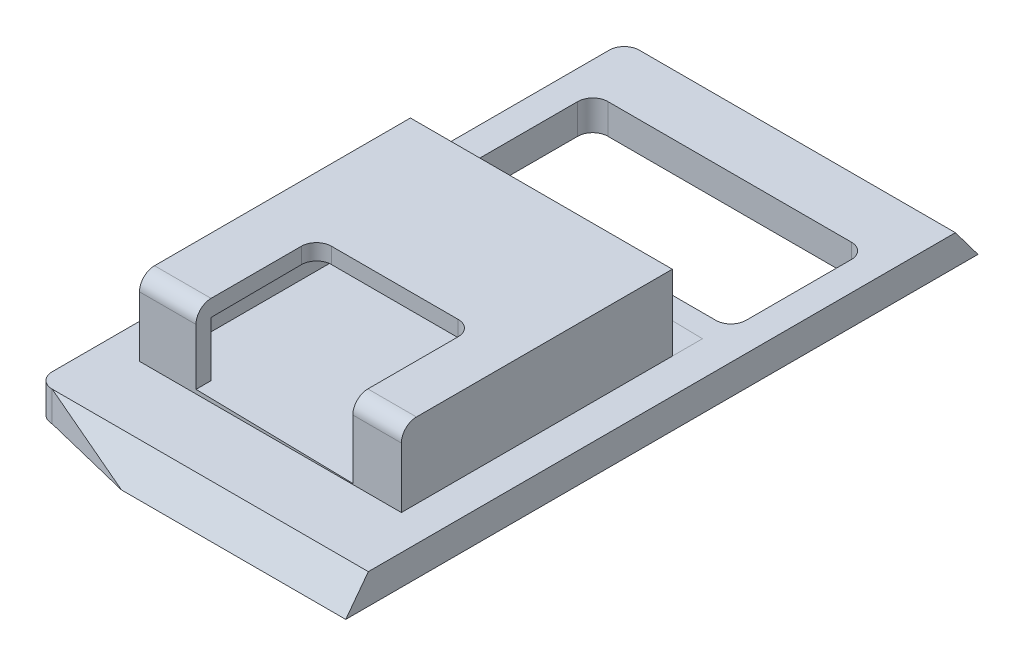
SolidWorks part; units mm, degrees
ref_plane "Alzado" through (0, 0, 0) normal (0, 0, 1) x (1, 0, 0)
ref_plane "Planta" through (0, 0, 0) normal (0, 1, 0) x (1, 0, 0)
ref_plane "Vista lateral" through (0, 0, 0) normal (1, 0, 0) x (0, 0, -1)
sketch "Croquis1" plane through (0, 0, 0) normal (0, 1, 0) x (1, 0, 0)
  line L1 (0, 0) -> (22, 0)
  line L2 (0, 0) -> (0, 39)
  line L3 (0, 39) -> (22, 39)
  line L4 (22, 0) -> (22, 39)
  line L5 (1.9117, 26) -> (20.0883, 26)
  line L6 (1.9117, 26) -> (1.9117, 35)
  line L7 (1.9117, 35) -> (20.0883, 35)
  line L8 (20.0883, 26) -> (20.0883, 35)
  line L22 (2.3, 4.4967) -> (19.7, 4.4967)
  line L23 (19.7, 4.4967) -> (19.7, 22.4967)
  line L24 (19.7, 22.4967) -> (18.7, 22.4967)
  line L25 (18.7, 22.4967) -> (18.7, 5.4967)
  line L26 (18.7, 5.4967) -> (3.3, 5.4967)
  line L27 (3.3, 5.4967) -> (3.3, 22.4967)
  line L28 (2.3, 4.4967) -> (2.3, 22.4967)
  line L29 (2.3, 22.4967) -> (3.3, 22.4967)
  dimension "D1" = 22
  dimension "D2" = 39
  dimension "D3" = 4
  dimension "D6" = 9
extrude "Saliente-Extruir1" add sketch "Croquis1" along normal blind 2
fillet "Redondeo1" radius 1 2 edges at (0, 1, 0) (0, 1, -39)
fillet "Redondeo2" radius 1 4 edges at (20.0883, 1, -26) (20.0883, 1, -35) (1.9117, 1, -26) (1.9117, 1, -35)
ref_plane "Plano4" through (3.3, 2, -22.4967) normal (-1, 0, 0) x (0, 0, 1)
sketch "Croquis8" plane through (0, 2, 0) normal (0, 1, 0) x (1, 0, 0)
  line L0 (2.3, 22.4967) -> (3.3, 22.4967)
  line L1 (3.3, 22.7717) -> (3.3, 22.2217) construction
  line L2 (3.3, 22.4967) -> (3.3, 5.4967)
  line L3 (3.3, 5.4967) -> (18.7, 5.4967)
  line L4 (18.7, 5.4967) -> (3.3, 5.4967) construction
  line L5 (18.7, 5.4967) -> (18.7, 22.4967)
  line L6 (18.7, 22.4967) -> (19.7, 22.4967)
  line L7 (19.7, 22.4967) -> (19.7, 4.4967)
  line L8 (19.7, 4.4967) -> (2.3, 4.4967)
  line L9 (2.3, 4.4967) -> (2.3, 22.4967)
extrude "Saliente-Extruir2" add sketch "Croquis8" along normal blind 5 separate body
sketch3d "Croquis3D1"
  line L0 (18.7, 7, -22.4967) -> (18.7, 2, -22.4967) construction
  line L1 (18.7, 6.0074, -22.4967) -> (18.7, 5.9008, -5.4967)
  line L2 (18.7, 7, -5.4967) -> (18.7, 2, -5.4967) construction
  line L3 (18.7, 5.9008, -5.4967) -> (18.7, 7, -5.4967)
  line L4 (18.7, 7, -5.4967) -> (18.7, 7, -22.4967)
  line L5 (18.7, 7, -22.4967) -> (18.7, 6.0074, -22.4967)
extrude "Saliente-Extruir4" add sketch "Croquis3D1" along direction (-1, 0, 0) on the side against the normal blind 15.4
sketch3d "Croquis3D2"
  line L0 (6.0546, 7, -4.4967) -> (6.0546, 2, -4.4967)
  line L1 (2.3, 7, -4.4967) -> (19.7, 7, -4.4967) construction
  line L2 (2.3, 2, -4.4967) -> (19.7, 2, -4.4967) construction
  line L3 (6.0546, 2, -4.4967) -> (16.4733, 2, -4.4967)
  line L4 (16.4733, 2, -4.4967) -> (16.4733, 7, -4.4967)
  line L5 (16.4733, 7, -4.4967) -> (6.0546, 7, -4.4967)
extrude "Cortar-Extruir2" cut sketch "Croquis3D2" along direction (0, 0, 1) on the side of the normal blind 8 contours L0 L3 L4 L5
fillet "Redondeo3" radius 1 4 edges
sketch "Croquis15" plane through (0, 0, -4.4967) normal (0, 0, -1) x (-1, 0, 0)
  line L0 (-19.7, 2) -> (-19.7, 0)
  line L1 (-19.7, 0) -> (-2.3, 0)
  line L2 (-2.3, 0) -> (-2.3, 2.3366)
  line L3 (-2.3, 2.3366) -> (-19.7, 2)
extrude "Saliente-Extruir5" add sketch "Croquis15" along normal blind 20
sketch "Croquis16" plane through (22, 0, 0) normal (1, 0, 0) x (0, 0, -1)
  line L0 (0, 0) -> (-1.5, 0)
  line L1 (-1.5, 0) -> (0, 2)
  line L2 (0, 2) -> (0, 0)
extrude "Saliente-Extruir6" add sketch "Croquis16" against normal blind 14.9
sketch "Croquis17" plane through (22, 0, 0) normal (1, 0, 0) x (0, 0, -1)
  line L0 (39, 0) -> (40.5, 0)
  line L1 (40.5, 0) -> (39, 2)
  line L2 (39, 2) -> (39, 0)
extrude "Saliente-Extruir7" add sketch "Croquis17" against normal blind 14.9
sketch "Croquis18" plane through (0, 0, 0) normal (0, -1, 0) x (1, 0, 0)
  line L0 (7.1, 1.5) -> (1, 0)
  line L1 (7.1, 1.5) -> (7.1, 0)
  line L2 (7.1, 0) -> (1, 0)
extrude "Saliente-Extruir8" add sketch "Croquis18" against normal blind 2
sketch "Croquis20" plane through (7.1, 0, 0) normal (1, 0, 0) x (0, 0, -1)
  line L0 (0, 2) -> (-1.5, 2)
  line L1 (-1.5, 2) -> (-1.5, 0)
  line L2 (-1.5, 0) -> (0, 2)
extrude "Cortar-Extruir3" cut sketch "Croquis20" against normal blind 7
sketch "Croquis22" plane through (0, 2, 0) normal (0, 1, 0) x (1, 0, 0)
  line L0 (7.1, 40.5) -> (7.1, 39)
  line L1 (7.1, 39) -> (1, 39)
  line L2 (1, 39) -> (7.1, 40.5)
extrude "Saliente-Extruir9" add sketch "Croquis22" against normal blind 2
sketch "Croquis23" plane through (7.1, 0, 0) normal (1, 0, 0) x (0, 0, -1)
  line L0 (40.5, 0) -> (39, 2)
  line L1 (39, 2) -> (40.5, 2)
  line L2 (40.5, 2) -> (40.5, 0)
extrude "Cortar-Extruir4" cut sketch "Croquis23" against normal blind 8
